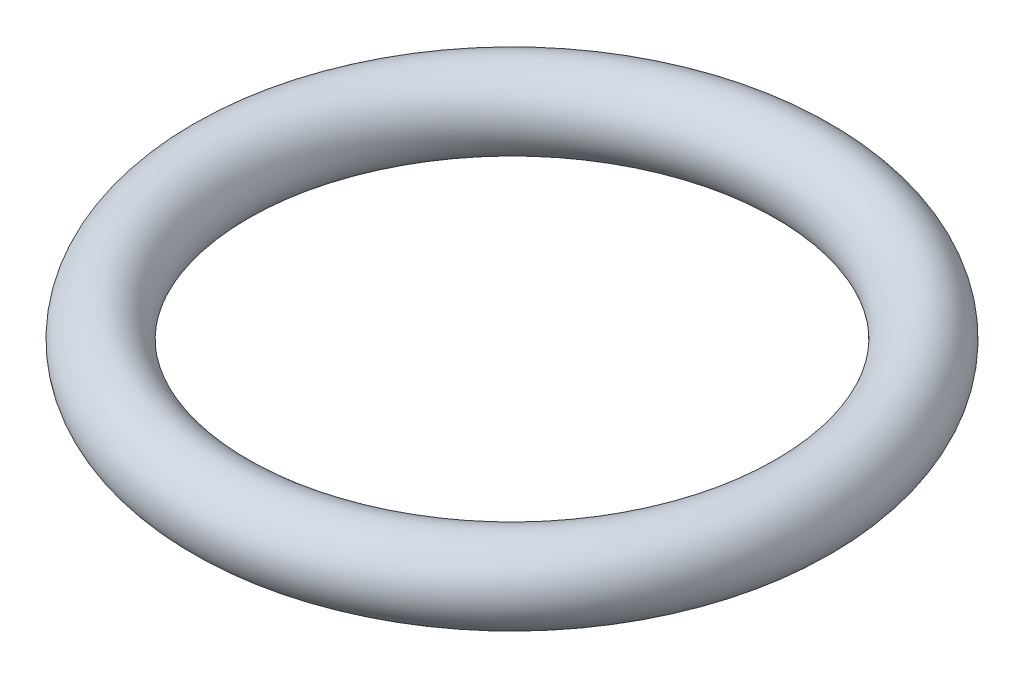
SolidWorks part; units mm, degrees
material "Rubber"
ref_plane "Front Plane" through (0, 0, 0) normal (0, 0, 1) x (1, 0, 0)
ref_plane "Top Plane" through (0, 0, 0) normal (0, 1, 0) x (1, 0, 0)
ref_plane "Right Plane" through (0, 0, 0) normal (1, 0, 0) x (0, 0, -1)
sketch "Sketch1" plane through (0, 0, 0) normal (0, 0, 1) x (1, 0, 0)
  line L0 (0, 9.122) -> (0, -13.4146) construction
  circle A0 centre (9.0932, 0) radius 1.2065
  dimension "D1" = 15.7734
  dimension "D2" = 2.413
revolve "Revolve1" add sketch "Sketch1" angle 360 about L0
